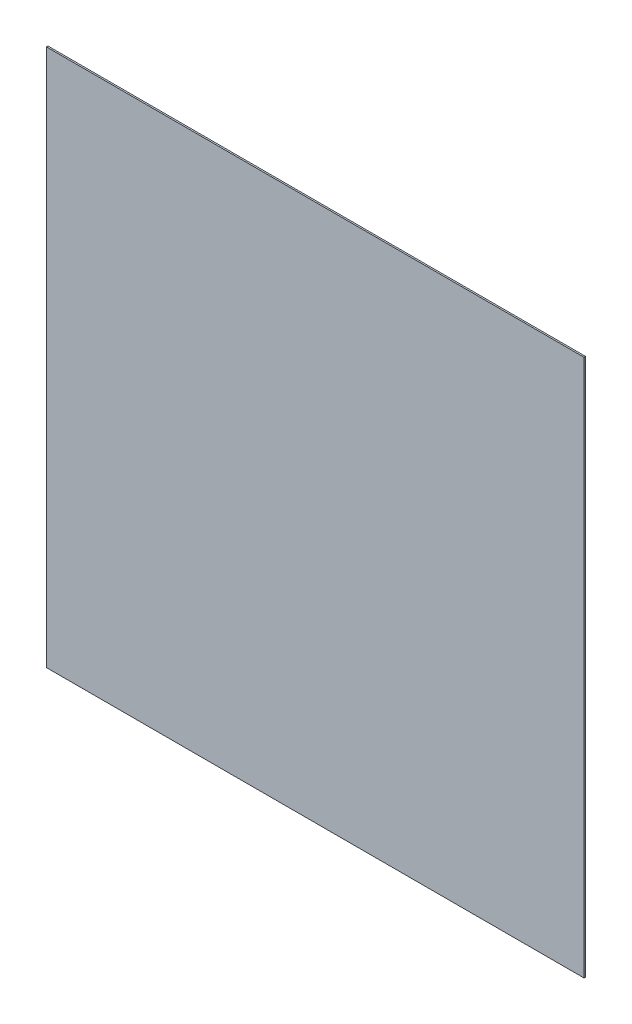
SolidWorks part; units mm, degrees
ref_plane "Plan de face" through (0, 0, 0) normal (0, 0, 1) x (1, 0, 0)
ref_plane "Plan de dessus" through (0, 0, 0) normal (0, 1, 0) x (1, 0, 0)
ref_plane "Plan de droite" through (0, 0, 0) normal (1, 0, 0) x (0, 0, -1)
sketch "Esquisse1" plane through (0, 0, 0) normal (0, 0, 1) x (1, 0, 0)
  line L4 (350, 350) -> (350, -350)
  line L5 (-350, -350) -> (350, -350)
  line L6 (-350, 350) -> (-350, -350)
  line L7 (350, 350) -> (-350, 350)
extrude "Boss.-Extru.1" add sketch "Esquisse1" along normal blind 2
